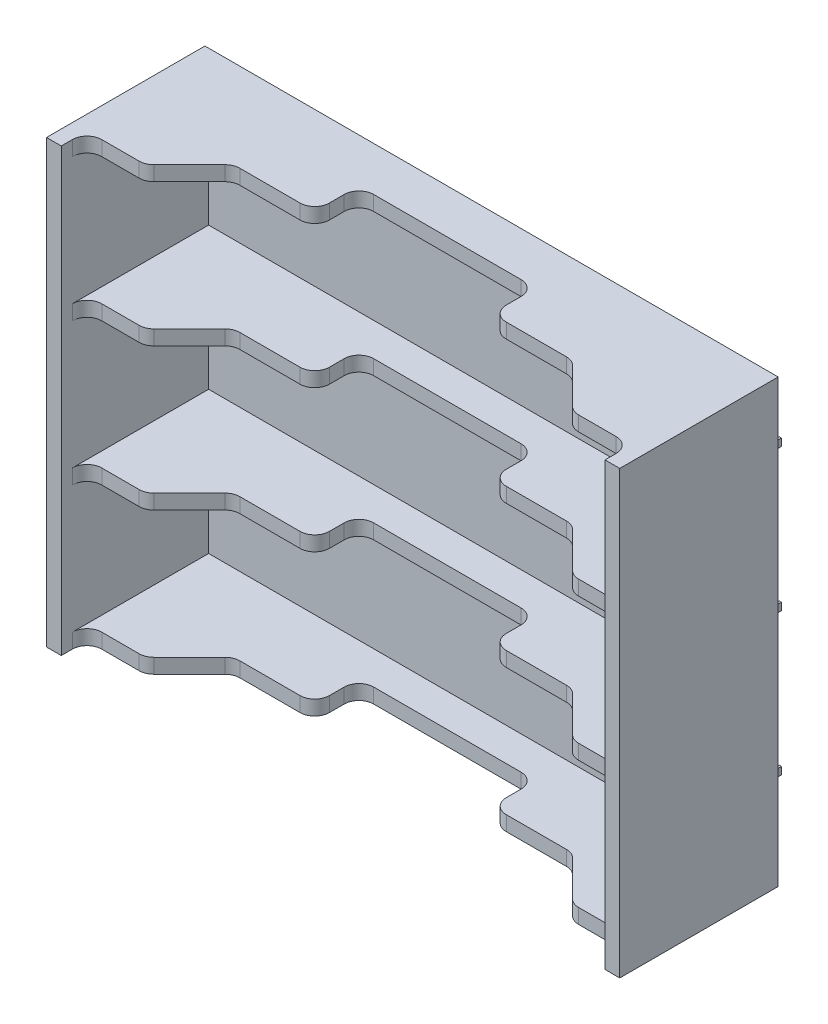
SolidWorks part; units mm, degrees
ref_plane "Front Plane" through (0, 0, 0) normal (0, 0, 1) x (1, 0, 0)
ref_plane "Top Plane" through (0, 0, 0) normal (0, 1, 0) x (1, 0, 0)
ref_plane "Right Plane" through (0, 0, 0) normal (1, 0, 0) x (0, 0, -1)
sketch "Sketch1" plane through (0, 0, 0) normal (0, 0, 1) x (1, 0, 0)
  line L1 (-38.9, 29.95) -> (38.9, 29.95)
  line L2 (-38.9, 29.95) -> (-38.9, -29.95)
  line L3 (-38.9, -29.95) -> (38.9, -29.95)
  line L4 (38.9, 29.95) -> (38.9, -29.95)
  line L5 (-38.9, 29.95) -> (38.9, -29.95) construction
  line L6 (-38.9, -29.95) -> (38.9, 29.95) construction
  point P0 (0, 0)
  dimension "D1" = 77.8
  dimension "D2" = 59.9
extrude "Boss-Extrude1" add sketch "Sketch1" along normal blind 21.5
sketch "Sketch2" plane through (0, -29.95, 0) normal (0, -1, 0) x (1, 0, 0)
  line L0 (0, 0) -> (0, 21.5) construction
  line L1 (-38.9, 21.5) -> (38.9, 21.5) construction
  line L2 (-36.9, 21.5) -> (36.9, 21.5)
  line L3 (36.9, 21.5) -> (36.9, 18)
  line L4 (36.9, 18) -> (29, 18)
  line L5 (29, 18) -> (23, 12)
  line L6 (23, 12) -> (12, 12)
  line L7 (12, 12) -> (12, 6)
  line L8 (12, 6) -> (-12, 6)
  line L10 (38.9, 21.5) -> (38.9, 0) construction
  line L11 (-38.9, 0) -> (38.9, 0) construction
  line L12 (-12, 12) -> (-12, 6)
  line L13 (-23, 12) -> (-12, 12)
  line L14 (-29, 18) -> (-23, 12)
  line L15 (-36.9, 18) -> (-29, 18)
  line L16 (-36.9, 21.5) -> (-36.9, 18)
  point P16 (22.564, 9)
  point P18 (0, 6)
  dimension "D1" = 2
  dimension "D2" = 45
  dimension "D3" = 6
  dimension "D4" = 6
  dimension "D5" = 6
  dimension "D6" = 12
  dimension "D7" = 11
extrude "Cut-Extrude1" cut sketch "Sketch2" against normal through all
fillet "Fillet1" radius 2 10 edges at (36.9, 0, 18) (29, 0, 18) (23, 0, 12) (12, 0, 6) (12, 0, 12) (-36.9, 0, 18) (-29, 0, 18) (-23, 0, 12) (-12, 0, 12) (-12, 0, 6)
sketch "Sketch4" plane through (0, 0, 21.5) normal (0, 0, 1) x (1, 0, 0)
  line L0 (-36.9, 29.95) -> (-36.9, -29.95) construction
  line L1 (-36.9, 27.95) -> (36.9, 27.95)
  line L2 (-36.9, 27.95) -> (-36.9, 10.65)
  line L3 (-36.9, 10.65) -> (36.9, 10.65)
  line L4 (36.9, 27.95) -> (36.9, 10.65)
  line L5 (36.9, 29.95) -> (36.9, -29.95) construction
  line L6 (36.9, 29.95) -> (36.9, -29.95) construction
  line L7 (36.9, 8.65) -> (-36.9, 8.65)
  line L8 (36.9, 8.65) -> (36.9, -8.65)
  line L9 (36.9, -8.65) -> (-36.9, -8.65)
  line L10 (-36.9, 8.65) -> (-36.9, -8.65)
  line L11 (-36.9, -10.65) -> (36.9, -10.65)
  line L12 (-36.9, -10.65) -> (-36.9, -27.95)
  line L13 (-36.9, -27.95) -> (36.9, -27.95)
  line L14 (36.9, -10.65) -> (36.9, -27.95)
  line L15 (29.8284, 29.95) -> (34.9, 29.95) construction
  line L16 (29.8284, -29.95) -> (34.9, -29.95) construction
  dimension "D1" = 2
  dimension "D2" = 2
  dimension "D3" = 2
  dimension "D4" = 2
extrude "Cut-Extrude2" cut sketch "Sketch4" against normal blind 20
sketch "Sketch5" plane through (0, 0, 1.5) normal (0, 0, 1) x (1, 0, 0)
  line L0 (0, 0) -> (-27.9, 0) construction
  line L1 (0, 27.95) -> (0, 10.65) construction
  line L2 (-38.9, 29.95) -> (-38.9, -29.95) construction
  line L3 (36.9, 27.95) -> (-36.9, 27.95) construction
  line L4 (10, 10.65) -> (-10, 10.65) construction
  line L5 (0, 19.3) -> (-27.9, 19.3) construction
  line L6 (-27.9, 19.3) -> (-27.9, 0) construction
  circle A0 centre (-27.9, 0) radius 1.75
  circle A1 centre (-27.9, 19.3) radius 1.75
  circle A2 centre (27.9, 0) radius 1.75
  circle A3 centre (27.9, 19.3) radius 1.75
  circle A4 centre (27.9, -19.3) radius 1.75
  circle A5 centre (-27.9, -19.3) radius 1.75
  dimension "D1" = 3.5
  dimension "D2" = 11
extrude "Cut-Extrude3" cut sketch "Sketch5" against normal through all
sketch "Sketch6" plane through (0, 0, 0) normal (0, 0, -1) x (-1, 0, 0)
  line L0 (-35.85, 0) -> (0, 0) construction
  line L1 (-36.15, 0.5) -> (-35.85, 0.5)
  line L2 (-36.15, 0.5) -> (-36.15, -0.5)
  line L3 (-36.15, -0.5) -> (-35.85, -0.5)
  line L4 (-35.85, 0.5) -> (-35.85, -0.5)
  line L5 (0, 0) -> (0, 19.3) construction
  line L6 (0, 19.3) -> (-36.15, 19.3) construction
  line L7 (0, 9.65) -> (-25.3073, 9.65) construction
  line L8 (-35.85, 18.8) -> (-35.85, 19.8)
  line L9 (-36.15, 19.8) -> (-35.85, 19.8)
  line L10 (-36.15, 18.8) -> (-36.15, 19.8)
  line L11 (-36.15, 18.8) -> (-35.85, 18.8)
  line L12 (36.15, 18.8) -> (35.85, 18.8)
  line L13 (36.15, 18.8) -> (36.15, 19.8)
  line L14 (36.15, 19.8) -> (35.85, 19.8)
  line L15 (35.85, 18.8) -> (35.85, 19.8)
  line L16 (35.85, 0.5) -> (35.85, -0.5)
  line L17 (36.15, -0.5) -> (35.85, -0.5)
  line L18 (36.15, 0.5) -> (36.15, -0.5)
  line L19 (36.15, 0.5) -> (35.85, 0.5)
  line L20 (35.85, -18.8) -> (35.85, -19.8)
  line L21 (36.15, -19.8) -> (35.85, -19.8)
  line L22 (36.15, -18.8) -> (36.15, -19.8)
  line L23 (36.15, -18.8) -> (35.85, -18.8)
  line L24 (-36.15, -18.8) -> (-35.85, -18.8)
  line L25 (-36.15, -18.8) -> (-36.15, -19.8)
  line L26 (-36.15, -19.8) -> (-35.85, -19.8)
  line L27 (-35.85, -18.8) -> (-35.85, -19.8)
  point P7 (-36, -0.5)
  dimension "D1" = 36
  dimension "D2" = 1
  dimension "D3" = 0.3
  dimension "D4" = 19.3
extrude "Boss-Extrude2" add sketch "Sketch6" along normal blind 3.2
